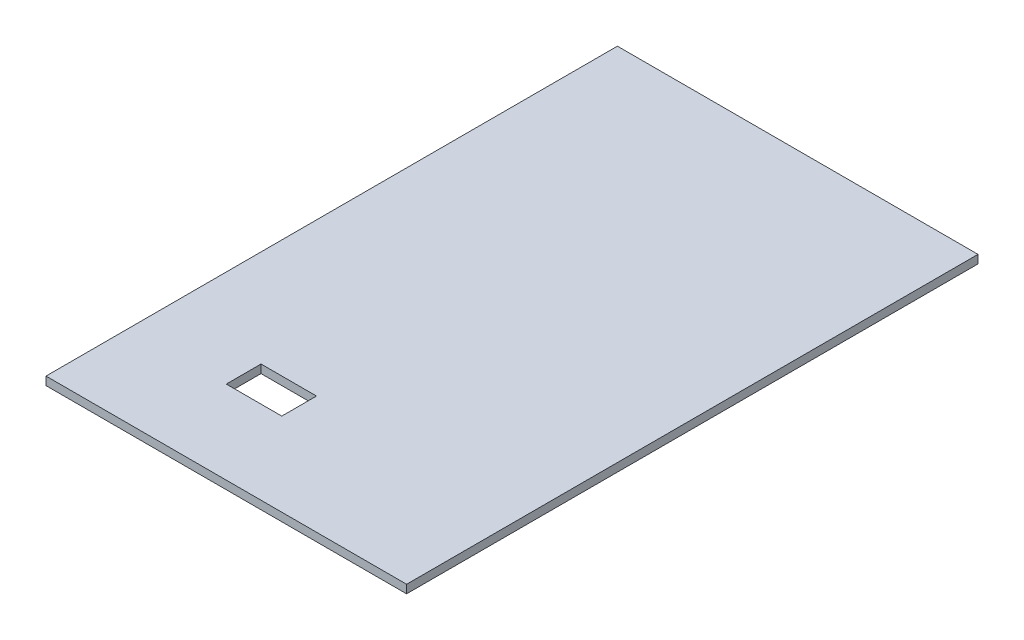
SolidWorks part; units mm, degrees
ref_plane "Front Plane" through (0, 0, 0) normal (0, 0, 1) x (1, 0, 0)
ref_plane "Top Plane" through (0, 0, 0) normal (0, 1, 0) x (1, 0, 0)
ref_plane "Right Plane" through (0, 0, 0) normal (1, 0, 0) x (0, 0, -1)
sketch "Sketch1" plane through (0, 0, 0) normal (0, 1, 0) x (1, 0, 0)
  line L1 (-65, 103) -> (65, 103)
  line L2 (-65, 103) -> (-65, -103)
  line L3 (-65, -103) -> (65, -103)
  line L4 (65, 103) -> (65, -103)
  line L5 (-65, 103) -> (65, -103) construction
  line L6 (-65, -103) -> (65, 103) construction
  point P0 (0, 0)
  dimension "D1" = 206
  dimension "D2" = 130
extrude "Boss-Extrude1" add sketch "Sketch1" along normal blind 3
sketch "Sketch3" plane through (0, 3, 0) normal (0, 1, 0) x (1, 0, 0)
  line L0 (-65, 103) -> (-65, -103) construction
  line L1 (-30, -60.48) -> (-10, -60.48)
  line L2 (-30, -60.48) -> (-30, -73)
  line L3 (-30, -73) -> (-10, -73)
  line L4 (-10, -60.48) -> (-10, -73)
  line L5 (-65, -103) -> (65, -103) construction
  dimension "D1" = 20
  dimension "D2" = 12.52
  dimension "D3" = 35
  dimension "D4" = 30
extrude "Cut-Extrude1" cut sketch "Sketch3" against normal blind 4
